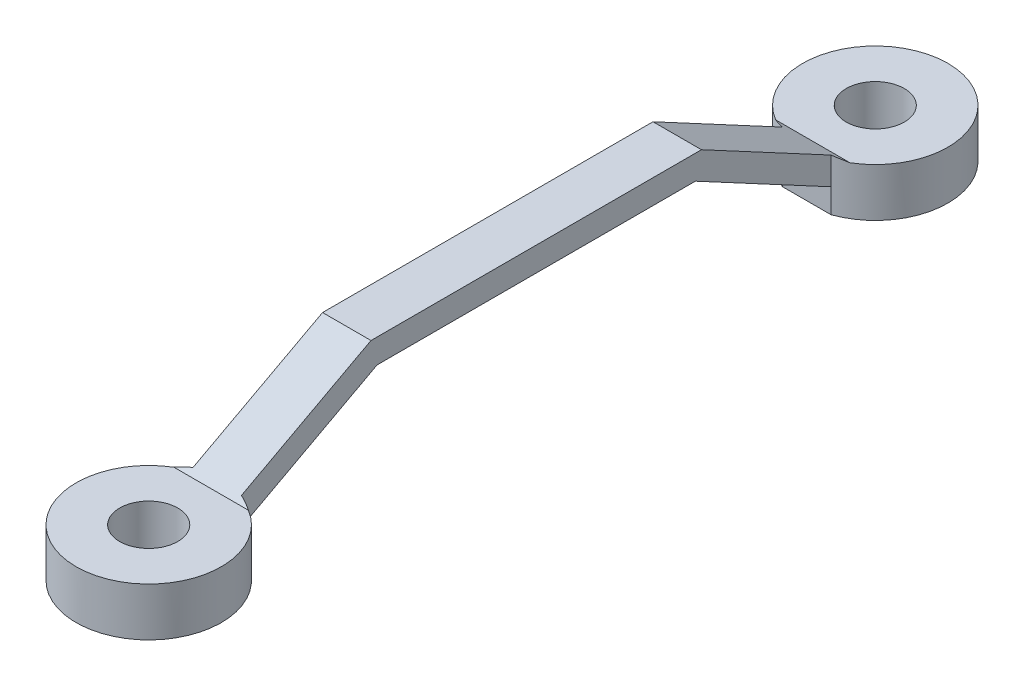
SolidWorks part; units mm, degrees
ref_plane "Front Plane" through (0, 0, 0) normal (0, 0, 1) x (1, 0, 0)
ref_plane "Top Plane" through (0, 0, 0) normal (0, 1, 0) x (1, 0, 0)
ref_plane "Right Plane" through (0, 0, 0) normal (1, 0, 0) x (0, 0, -1)
sketch "Sketch1" plane through (0, 0, 0) normal (0, 1, 0) x (1, 0, 0)
  line L17 (1, -15) -> (1, 15) construction
  line L45 (2, -12.1716) -> (2, 12.1716)
  line L47 (0, -12.1716) -> (0, 12.1716)
  line L50 (0, -15) -> (0, 15) construction
  line L51 (2, -15) -> (2, 15) construction
  arc A12 (2, -12.1716) -> (0, -12.1716) centre (1, -15) cw
  arc A13 (2, 12.1716) -> (0, 12.1716) centre (1, 15) ccw
  point P0 (0, 0)
  dimension "D2" = 3
  dimension "D3" = 3
  dimension "D4" = 24.3431
  dimension "D5" = 0
  dimension "D6" = 2
  dimension "D11" = 30
extrude "Boss-Extrude1" add sketch "Sketch1" along normal blind 10
sketch "Sketch2" plane through (2, 0, 0) normal (1, 0, 0) x (0, 0, -1)
  line L0 (0, 0) -> (0, 5) construction
  line L1 (18, 0) -> (18, 10) construction
  line L2 (6.5713, 4) -> (-6.5713, 4)
  line L3 (18, 0) -> (18, 2)
  line L4 (-12.1716, 1) -> (-12.1716, 0)
  line L5 (-12.1716, 1) -> (-12.1716, 0)
  line L6 (6.5713, 4) -> (12.1716, 1)
  line L7 (-12.4225, 2) -> (-18, 2)
  line L8 (6.8223, 5) -> (12.4225, 2)
  line L9 (12.4225, 2) -> (18, 2)
  line L10 (6.8223, 5) -> (-6.8223, 5)
  line L11 (7.0435, 4.8815) -> (12.4225, 2) construction
  line L12 (12.1716, 5) -> (-20.0709, 5) construction
  line L13 (12.1716, 4) -> (-20.0709, 4) construction
  line L14 (12.1716, 1) -> (12.1716, 0)
  line L15 (12.1716, 1) -> (18, 1) construction
  line L16 (-6.8223, 5) -> (-12.4225, 2)
  line L17 (-6.5713, 4) -> (-12.1716, 1)
  line L18 (-18, 0) -> (-18, 2)
  line L19 (12.1716, 0) -> (18, 0) construction
  line L20 (-18, 0) -> (-12.1716, 0) construction
  line L21 (12.1716, 0) -> (18, 0)
  line L22 (-18, 0) -> (-12.1716, 0)
  line L23 (12.1716, 10) -> (12.1716, 0) construction
  line L25 (12.1716, 1) -> (12.1716, 0)
  line L27 (12.4225, 2) -> (18, 2) construction
  point P25 (0, 4)
  point P29 (0, 0)
  point P30 (0, 0)
  line M17 (12.1716, 0) -> (12.1716, 10)
  line M19 (-12.1716, 10) -> (-12.1716, 0)
  dimension "D1" = 2
  dimension "D2" = 1
  dimension "D3" = 1
  dimension "D4" = 1
extrude "Cut-Extrude1" cut sketch "Sketch2" against normal blind 10 and the other way through all flip side to cut contours L17 L2 L6 L8 L10 L16 M17 M19 | L21 L3 L9 L8 M17 | L18 L22 L16 L7 M19
sketch "Sketch3" plane through (0, 2, 0) normal (0, 1, 0) x (1, 0, 0)
  line L0 (2.5352, -12.4225) -> (-0.5352, -12.4225) construction
  line L1 (-0.5352, 12.4225) -> (2.5352, 12.4225) construction
  line L2 (2.5352, -12.4225) -> (-0.5352, -12.4225)
  line L3 (-0.5352, 12.4225) -> (2.5352, 12.4225)
  arc A0 (-0.5352, -12.4225) -> (2.5352, -12.4225) centre (1, -15) ccw construction
  arc A1 (2.5352, 12.4225) -> (-0.5352, 12.4225) centre (1, 15) ccw construction
  arc A2 (-0.5352, -12.4225) -> (2.5352, -12.4225) centre (1, -15) ccw
  arc A3 (2.5352, 12.4225) -> (-0.5352, 12.4225) centre (1, 15) ccw
  point P2 (1, -15)
  point P3 (1, 15)
hole_wizard "M2 Clearance Hole1" positions "Sketch3" profile "Sketch4" hole size "M2" standard "ISO" end condition through all
sketch "Sketch4" plane through (1, 2, -15) normal (1, 0, 0) x (0, 0, 1)
  line L0 (0, 0) -> (0, 2)
  line L1 (0, 2) -> (1.2, 2)
  line L2 (1.2, 2) -> (1.2, 0)
  line L5 (1.2, 0) -> (0, 0)
  line L11 (0, -6.35) -> (0, 107.95) construction
  dimension "Thru Hole Dia." = 2.4
  dimension "Thru Hole Depth" = 2
